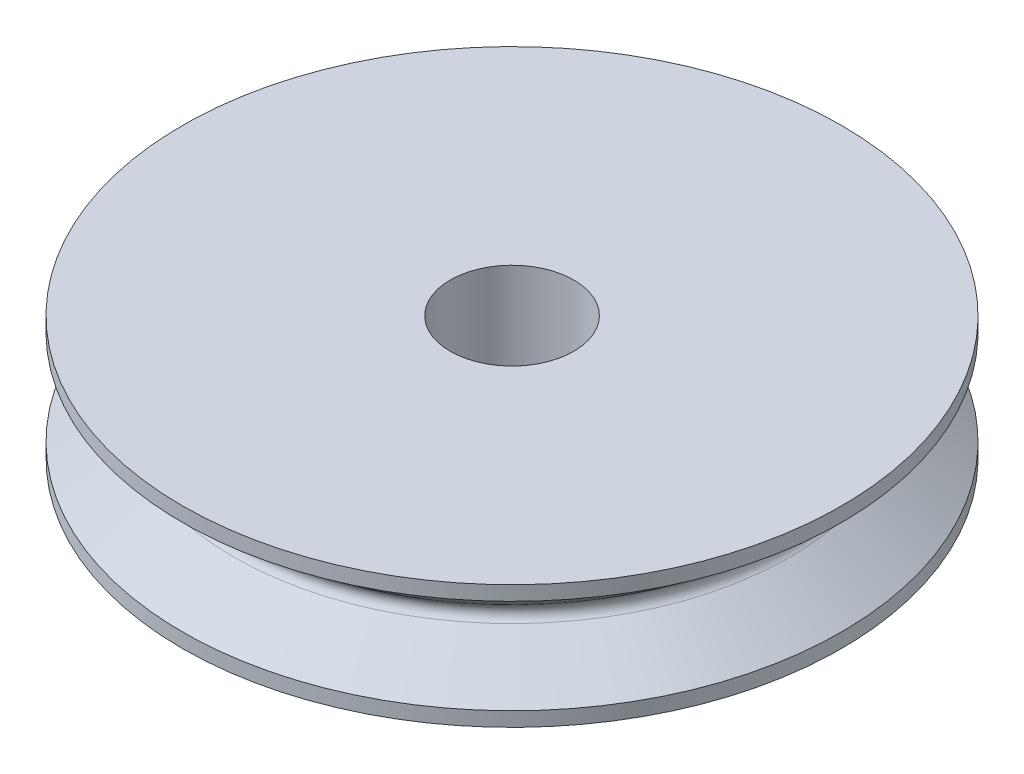
SolidWorks part; units mm, degrees
ref_plane "Спереди" through (0, 0, 0) normal (0, 0, 1) x (1, 0, 0)
ref_plane "Сверху" through (0, 0, 0) normal (0, 1, 0) x (1, 0, 0)
ref_plane "Справа" through (0, 0, 0) normal (1, 0, 0) x (0, 0, -1)
sketch "Эскиз1" plane through (0, 0, 0) normal (0, 1, 0) x (1, 0, 0)
  circle A0 centre (0, 0) radius 16
extrude "Вытянуть1" add sketch "Эскиз1" along normal blind 6
sketch "Эскиз2" plane through (0, 0, 0) normal (0, 0, 1) x (1, 0, 0)
  line L0 (16, 3) -> (20.2388, 3) construction
  line L1 (16, 0.7) -> (13.5084, 2.6026)
  line L2 (16, 5.3) -> (18.5722, 5.3) construction
  line L3 (0, 0) -> (0, 10.8486) construction
  line L4 (16, 6) -> (-16, 6) construction
  line L5 (16, 5.3) -> (13.5084, 3.3974)
  line L6 (16, 0) -> (16, 6) construction
  line L7 (16, 5.3) -> (16, 0.7)
  arc A0 (13.5084, 2.6026) -> (13.5084, 3.3974) centre (13.8119, 3) cw
  point P13 (12.988, 3)
  dimension "D2" = 0.5
  dimension "D1" = 0.7
revolve "Вырез-Повернуть1" cut sketch "Эскиз2" angle 360 about L3
sketch "Эскиз4" plane through (0, 6, 0) normal (0, 1, 0) x (1, 0, 0)
  circle A0 centre (0, 0) radius 3
extrude "Вытянуть2" cut sketch "Эскиз4" against normal through all
